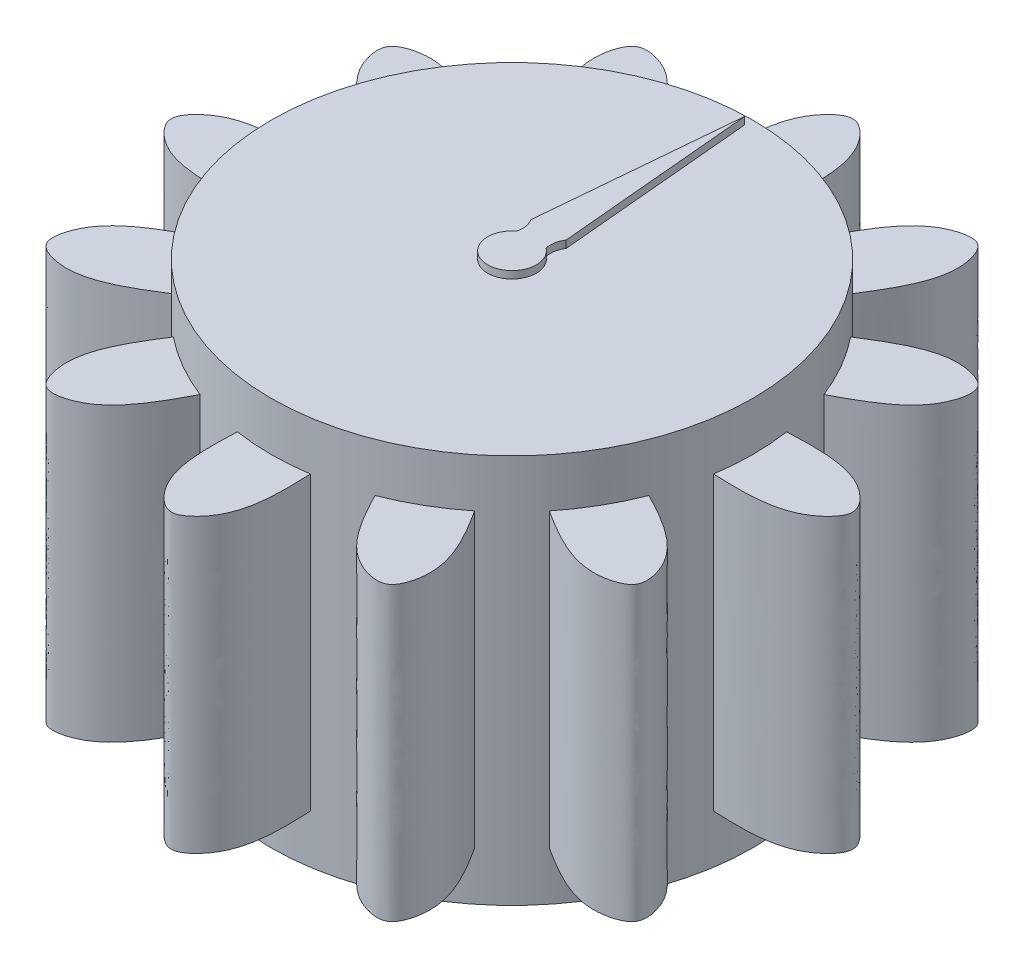
SolidWorks part; units mm, degrees
ref_plane "Front Plane" through (0, 0, 0) normal (0, 0, 1) x (1, 0, 0)
ref_plane "Top Plane" through (0, 0, 0) normal (0, 1, 0) x (1, 0, 0)
ref_plane "Right Plane" through (0, 0, 0) normal (1, 0, 0) x (0, 0, -1)
sketch "Sketch1" plane through (0, 0, 0) normal (0, 1, 0) x (1, 0, 0)
  line L0 (0, 0) -> (0, 10) construction
  circle A12 centre (0, 0) radius 9.9
  point P43 (0, 0)
  dimension "D1" = 19.8
extrude "Boss-Extrude1" add sketch "Sketch1" along normal blind 12
sketch "Sketch4" plane through (0, 0, 0) normal (0, -1, 0) x (1, 0, 0)
  line L0 (-1.5, -9.7857) -> (1.5, -9.7857)
  circle A1 centre (0, 0) radius 9.9 construction
  spline S0 degree 3 poles (1.5, -9.7857) (1.5223, -10.3509) (1.5744, -11.6677) (1.1993, -13.2812) (0, -14.189) (-1.1993, -13.2812) (-1.5744, -11.6677) (-1.5223, -10.3509) (-1.5, -9.7857) knots 0 0 0 0 0.178316 0.415433 0.5 0.584567 0.821684 1 1 1 1
  point P2 (0, 0)
  dimension "D1" = 3
  dimension "D2" = 3
  dimension "D3" = 14
  dimension "D4" = 1.4
  dimension "D5" = 0.4
  dimension "D6" = 0.7
  dimension "D7" = 1.7
  dimension "D8" = 4.2143
sketch "Sketch2" plane through (0, 12, 0) normal (0, 1, 0) x (1, 0, 0)
  circle A0 centre (0, 0) radius 9.9
  dimension "D1" = 19.8
extrude "Boss-Extrude2" add sketch "Sketch2" along normal blind 2
sketch "Sketch3" plane through (0, 14, 0) normal (0, 1, 0) x (1, 0, 0)
  line L0 (0, 0) -> (0, 1) construction
  line L2 (0, 1) -> (0, 9.5619) construction
  line L3 (0, 9.5619) -> (0.7279, 1.5)
  line L4 (0, 9.5619) -> (-0.7174, 1.5002)
  arc A0 (-0.6, 0.8) -> (0.6, 0.8) centre (0, 0) ccw
  arc A1 (0.7279, 1.5) -> (0.6, 0.8) centre (1.5527, 0.9877) ccw
  arc A2 (-0.7174, 1.5002) -> (-0.6, 0.8) centre (-1.55, 1.0007) cw
  point P6 (0.7279, 1.5)
  dimension "D1" = 2
  dimension "D3" = 0.971
  dimension "D6" = 8.5619
  dimension "D2" = 1.2
  dimension "D4" = 0.7116
  dimension "D5" = 0.71
  dimension "D7" = 0.9527
  dimension "D8" = 0.95
  dimension "D9" = 1.8402
extrude "Boss-Extrude3" add sketch "Sketch3" along normal blind 0.3 contours A1 A0 A2 L4 L3
extrude "Boss-Extrude5" add sketch "Sketch4" against normal blind 12
pattern_circular "CirPattern1" count 12 over 360 about axis through (0, 0, 0) along (0, 1, 0) of "Boss-Extrude5"
sketch "Sketch5" plane through (0, 0, 0) normal (0, -1, 0) x (1, 0, 0)
  circle A0 centre (0, 0) radius 9.9
  dimension "D1" = 19.8
extrude "Boss-Extrude6" add sketch "Sketch5" along normal blind 2
sketch "Sketch6" plane through (0, -2, 0) normal (0, -1, 0) x (1, 0, 0)
  line L0 (0, -9.5619) -> (0.7279, -1.5) construction
  line L1 (0, -9.5619) -> (-0.7174, -1.5002) construction
  line L2 (0, -9.5619) -> (0.7279, -1.5)
  line L3 (0, -9.5619) -> (-0.7174, -1.5002)
  arc A0 (0.6, -0.8) -> (0.7279, -1.5) centre (1.5527, -0.9877) ccw construction
  arc A1 (0.6, -0.8) -> (-0.6, -0.8) centre (0, 0) ccw construction
  arc A2 (-0.7174, -1.5002) -> (-0.6, -0.8) centre (-1.55, -1.0007) ccw construction
  arc A3 (0.6, -0.8) -> (0.7279, -1.5) centre (1.5527, -0.9877) ccw
  arc A4 (0.6, -0.8) -> (-0.6, -0.8) centre (0, 0) ccw
  arc A5 (-0.7174, -1.5002) -> (-0.6, -0.8) centre (-1.55, -1.0007) ccw
extrude "Boss-Extrude7" add sketch "Sketch6" along normal blind 0.3
